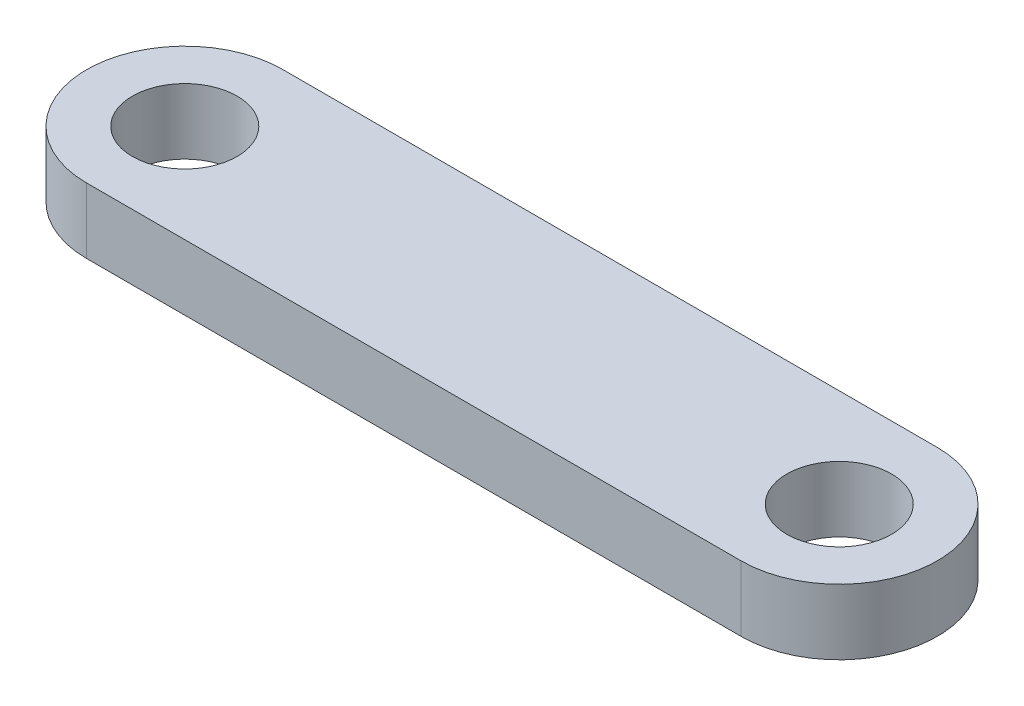
SolidWorks part; units mm, degrees
ref_plane "Front Plane" through (0, 0, 0) normal (0, 0, 1) x (1, 0, 0)
ref_plane "Top Plane" through (0, 0, 0) normal (0, 1, 0) x (1, 0, 0)
ref_plane "Right Plane" through (0, 0, 0) normal (1, 0, 0) x (0, 0, -1)
sketch "Sketch1" plane through (0, 0, 0) normal (0, 1, 0) x (1, 0, 0)
  line L0 (0, 0) -> (50, 0) construction
  line L1 (0, 7.5) -> (50, 7.5)
  line L2 (0, -7.5) -> (50, -7.5)
  arc A0 (0, 7.5) -> (0, -7.5) centre (0, 0) ccw
  arc A1 (50, -7.5) -> (50, 7.5) centre (50, 0) ccw
  circle A2 centre (0, 0) radius 4
  circle A3 centre (50, 0) radius 4
  point P3 (25, 0)
  dimension "D2" = 7.5
  dimension "D3" = 8
  dimension "D1" = 50
extrude "Boss-Extrude1" add sketch "Sketch1" along normal mid plane 5
